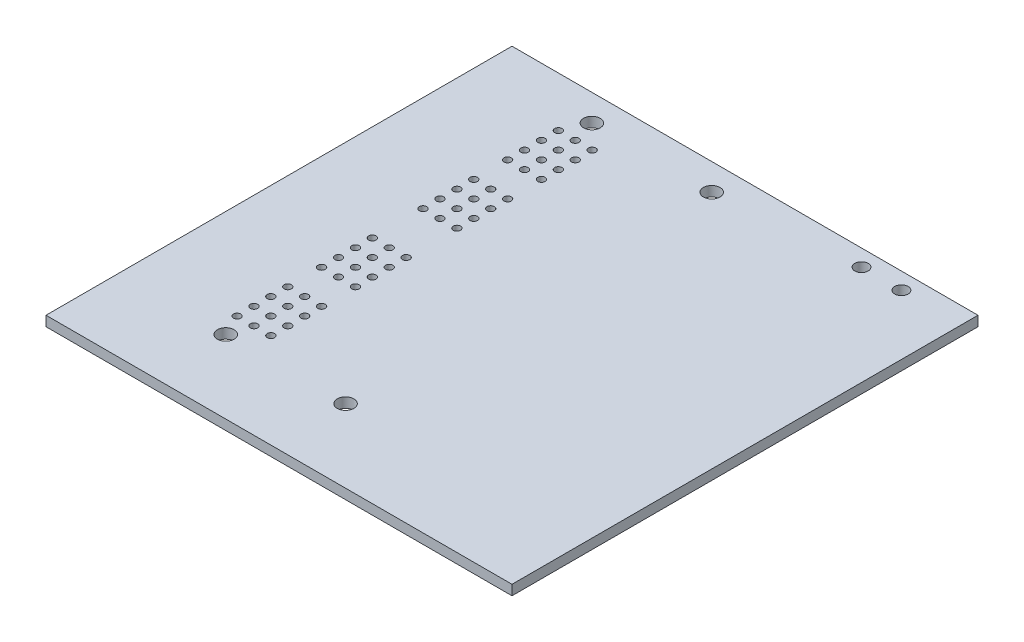
SolidWorks part; units mm, degrees
ref_plane "Plano frontal" through (0, 0, 0) normal (0, 0, 1) x (1, 0, 0)
ref_plane "Plano superior" through (0, 0, 0) normal (0, 1, 0) x (1, 0, 0)
ref_plane "Plano direito" through (0, 0, 0) normal (1, 0, 0) x (0, 0, -1)
sketch "Esboço1" plane through (0, 0, 0) normal (0, 1, 0) x (1, 0, 0)
  line L0 (20, 32.5) -> (26, 32.5) construction
  line L1 (-35, -35) -> (35, -35)
  line L2 (-35, -35) -> (-35, 35)
  line L3 (-35, 35) -> (35, 35)
  line L4 (35, -35) -> (35, 35)
  line L5 (-35, -35) -> (35, 35) construction
  line L6 (-35, 35) -> (35, -35) construction
  line L7 (-19, 31) -> (-1, 31) construction
  line L8 (-19, 31) -> (-19, -24) construction
  line L9 (-19, -24) -> (-1, -24) construction
  line L10 (-1, 31) -> (-1, -24) construction
  circle A0 centre (-19, 31) radius 1.25
  circle A1 centre (-1, 31) radius 1.25
  circle A2 centre (-1, -24) radius 1.25
  circle A3 centre (-19, -24) radius 1.25
  circle A4 centre (20, 32.5) radius 1
  circle A5 centre (26, 32.5) radius 1
  point P0 (0, 0)
  dimension "D2" = 2.5
  dimension "D7" = 2
  dimension "D10" = 9
  dimension "D1" = 70
  dimension "D3" = 4
  dimension "D4" = 11
  dimension "D5" = 16
  dimension "D6" = 1
  dimension "D8" = 6
  dimension "D9" = 2.5
extrude "Ressalto-extrusão1" add sketch "Esboço1" along normal blind 1.5
sketch "Esboço2" plane through (0, 1.5, 0) normal (0, 1, 0) x (1, 0, 0)
  line L0 (-20.54, 27.5) -> (-15.46, 27.5) construction
  line L1 (-19, 27.5) -> (-19, 31) construction
  circle A0 centre (-20.54, 27.5) radius 0.55
  circle A1 centre (-18, 27.5) radius 0.55
  circle A2 centre (-15.46, 27.5) radius 0.55
  circle A3 centre (-19, 31) radius 1.25 construction
  point P7 (-18, 27.5)
  point P11 (-16.4099, 21.7761)
  dimension "D1" = 1.1
  dimension "D2" = 2.54
  dimension "D3" = 1
  dimension "D4" = 3.5
extrude "Corte-extrusão1" cut sketch "Esboço2" against normal through all
pattern_linear "Padrão linear2" [suppressed] count 2 spacing 13.5 count 2 spacing 11
pattern_linear "Padrão linear1" count 20 spacing 2.54 along (0, 0, 1) skipping (4, 0), (9, 0), (10, 0), (15, 0) of "Corte-extrusão1"
